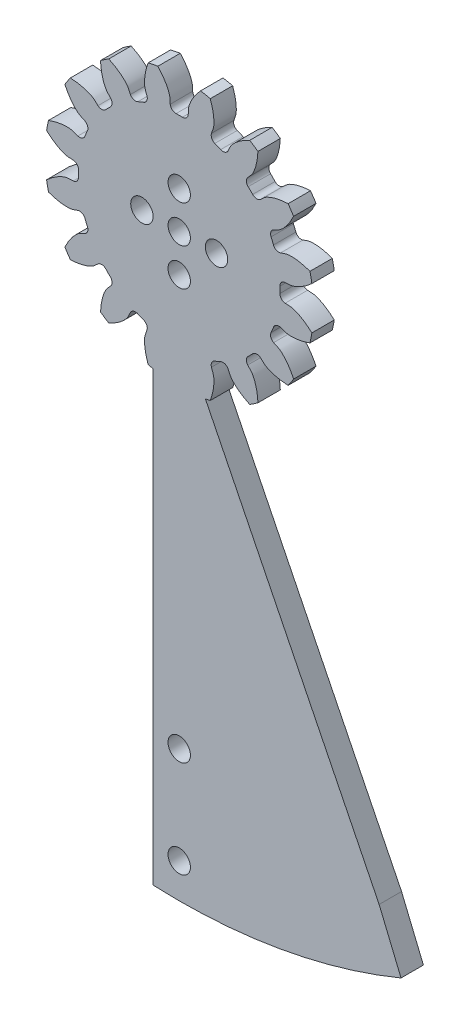
SolidWorks part; units mm, degrees
ref_plane "Front" through (0, 0, 0) normal (0, 0, 1) x (1, 0, 0)
ref_plane "Top" through (0, 0, 0) normal (0, 1, 0) x (1, 0, 0)
ref_plane "Right" through (0, 0, 0) normal (1, 0, 0) x (0, 0, -1)
ref_axis "Axis1" through (0, 0, -80.9) along (0, 0, 1)
sketch "草图1" plane through (0, 0, 0) normal (0, 0, 1) x (1, 0, 0)
  circle A0 centre (0, 0) radius 18
extrude "LaShenA" add sketch "草图1" along normal blind 3
sketch "SketchA" plane through (0, 0, 3) normal (0, 0, 1) x (1, 0, 0)
  line L0 (0, 0) -> (0, 18) construction
  arc A0 (0.4232, 13.4934) -> (-0.4232, 13.4934) centre (0, 0) ccw
  arc A1 (3.858, 18.7275) -> (-3.858, 18.7275) centre (0, 0) ccw
  arc A2 (-0.4232, 13.4934) -> (-1.2044, 14.1898) centre (-0.447, 14.253) cw
  arc A3 (1.2044, 14.1898) -> (0.4232, 13.4934) centre (0.447, 14.253) cw
  circle A4 centre (0, 0) radius 15.0351 construction
  circle A5 centre (0, 0) radius 18 construction
  circle A6 centre (0, 0) radius 13.5 construction
  circle A7 centre (0, 0) radius 16 construction
  spline S0 degree 3 poles (1.2044, 14.1898) (1.2266, 14.4552) (1.2138, 14.7739) (1.2737, 15.1106) (1.2991, 15.2114) (1.3214, 15.2911) (1.3499, 15.3823) (1.3851, 15.4846) (1.4278, 15.5978) (1.4786, 15.7214) (1.5382, 15.8552) (1.6071, 15.9987) (1.686, 16.1514) (1.7754, 16.3129) (1.876, 16.4827) (1.9884, 16.6603) (2.1129, 16.8451) (2.2502, 17.0365) (2.4007, 17.234) (2.5649, 17.4369) (2.7432, 17.6446) (2.9361, 17.8564) (3.1439, 18.0718) (3.4474, 18.3685) (3.6895, 18.585) (3.858, 18.7275) knots 0.122308 0.122308 0.122308 0.122308 0.250611 0.276296 0.287604 0.300968 0.316388 0.333864 0.353395 0.374983 0.398627 0.424327 0.452082 0.481894 0.513762 0.547685 0.583665 0.6217 0.661792 0.703939 0.748143 0.794402 0.842718 0.893089 1 1 1 1
  spline S1 degree 3 poles (-1.2044, 14.1898) (-1.2266, 14.4552) (-1.2138, 14.7739) (-1.2737, 15.1106) (-1.2991, 15.2114) (-1.3214, 15.2911) (-1.3499, 15.3823) (-1.3851, 15.4846) (-1.4278, 15.5978) (-1.4786, 15.7214) (-1.5382, 15.8552) (-1.6071, 15.9987) (-1.686, 16.1514) (-1.7754, 16.3129) (-1.876, 16.4827) (-1.9884, 16.6603) (-2.1129, 16.8451) (-2.2502, 17.0365) (-2.4007, 17.234) (-2.5649, 17.4369) (-2.7432, 17.6446) (-2.9361, 17.8564) (-3.1439, 18.0718) (-3.4474, 18.3685) (-3.6895, 18.585) (-3.858, 18.7275) knots 0.122308 0.122308 0.122308 0.122308 0.250611 0.276296 0.287604 0.300968 0.316388 0.333864 0.353395 0.374983 0.398627 0.424327 0.452082 0.481894 0.513762 0.547685 0.583665 0.6217 0.661792 0.703939 0.748143 0.794402 0.842718 0.893089 1 1 1 1
  dimension "D1" = 0.76
  dimension "Db" = 30.0702
  dimension "Da" = 36
  dimension "Df" = 27
  dimension "Dn" = 32
extrude "Cut-ExtrudeA" cut sketch "SketchA" against normal blind 3
pattern_circular "www.KYTool.cn" count 16 over 360 about axis through (0, 0, -80.9) along (0, 0, 1) of "Cut-ExtrudeA"
sketch "草图3" plane through (0, 0, 0) normal (0, 0, -1) x (-1, 0, 0)
  circle A0 centre (0, 0) radius 1.5
extrude "切除-拉伸2" cut sketch "草图3" against normal blind 10
sketch "草图4" plane through (0, 0, 0) normal (0, 0, -1) x (-1, 0, 0)
  line L0 (0, 0) -> (5, 0)
  circle A0 centre (5, 0) radius 1.5
  circle A1 centre (0, -5) radius 1.5
  circle A2 centre (-5, 0) radius 1.5
  circle A3 centre (0, 5) radius 1.5
  point P13 (0, 0)
  dimension "D1" = 4
extrude "切除-拉伸3" cut sketch "草图4" against normal blind 10
sketch "草图5" plane through (0, 0, 0) normal (0, 0, -1) x (-1, 0, 0)
  line L0 (-3.5116, -17.6541) -> (-3.5116, -77.6541)
  line L1 (3.5116, -17.6541) -> (3.5116, -77.6541)
  line L3 (0, 0) -> (-5.1662, -12.4724)
  line L4 (-5.1662, -12.4724) -> (-6.8883, -16.6298)
  line L5 (-6.8883, -16.6298) -> (-29.717, -71.7431)
  line L6 (-3.5116, -17.6541) -> (3.5116, -17.6541)
  line L7 (-3.5116, -17.6541) -> (-3.5116, -11.9836)
  line L8 (3.5116, -17.6541) -> (3.5116, -11.9836)
  line L9 (-3.5116, -11.9836) -> (3.5116, -11.9836)
  circle A1 centre (0, 0) radius 18
  arc A2 (2.8593, -17.7715) -> (4.1592, -17.5129) centre (0, 0) ccw construction
  arc A3 (-4.1592, -17.5129) -> (-2.8593, -17.7715) centre (0, 0) ccw construction
  arc A5 (-5.5547, -12.3043) -> (-4.7727, -12.6282) centre (0, 0) ccw construction
  circle A6 centre (0, 0) radius 77.6541
  circle A7 centre (0, 0) radius 70
extrude "凸台-拉伸3" add sketch "草图5" against normal blind 3 contours L9 L7 L6 L8 | L0 A7 L1 A1 | A7 L0 A6 L1 | A7 L5 A6 L0 | L6 A1
sketch "草图6" plane through (0, 0, 3) normal (0, 0, 1) x (1, 0, 0)
  circle A2 centre (0, -60) radius 1.5
  circle A3 centre (0, -73) radius 1.5
extrude "切除-拉伸4" cut sketch "草图6" against normal blind 3
sketch "草图7" plane through (0, 0, 3) normal (0, 0, 1) x (1, 0, 0)
  line L0 (26.7878, -64.6716) -> (3.5116, -17.6541)
  line L1 (3.5116, -17.6541) -> (3.5116, -69.9119)
  line L2 (3.5116, -69.9119) -> (15.3746, -76.1169)
  line L3 (15.3746, -76.1169) -> (26.7878, -64.6716)
  arc A0 (-3.5116, -77.5747) -> (29.717, -71.7431) centre (0, 0) ccw construction
extrude "凸台-拉伸4" add sketch "草图7" against normal blind 3
